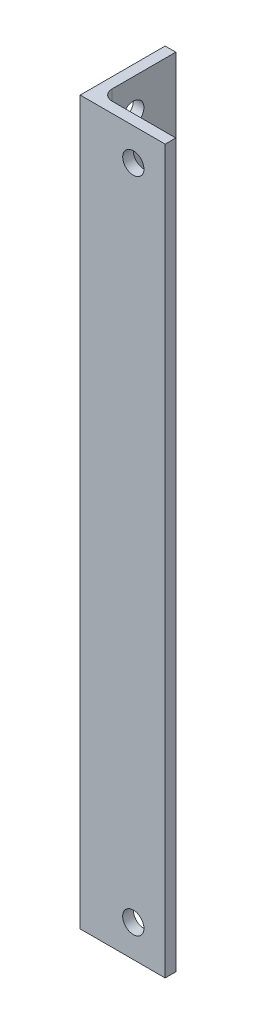
SolidWorks part; units mm, degrees
ref_plane "Front" through (0, 0, 0) normal (0, 0, 1) x (1, 0, 0)
ref_plane "Top" through (0, 0, 0) normal (0, 1, 0) x (1, 0, 0)
ref_plane "Right" through (0, 0, 0) normal (1, 0, 0) x (0, 0, -1)
sketch "Sketch1" plane through (0, 0, 0) normal (0, 1, 0) x (1, 0, 0)
  line L0 (0, 0) -> (0, -25.4)
  line L1 (0, -25.4) -> (25.4, -25.4)
  line L2 (25.4, -25.4) -> (25.4, -22.225)
  line L3 (25.4, -22.225) -> (3.175, -22.225)
  line L4 (3.175, -22.225) -> (3.175, 0)
  line L5 (3.175, 0) -> (0, 0)
  dimension "D1" = 3.175
  dimension "D2" = 25.4
  dimension "D3" = 25.4
  dimension "D4" = 3.175
extrude "Boss-Extrude1" add sketch "Sketch1" along normal blind 215.9
fillet "Fillet1" radius 3.175 1 edges at (3.175, 107.95, 22.225)
sketch "Sketch2" plane through (0, 0, 22.225) normal (0, 0, -1) x (-1, 0, 0)
  line L0 (-25.4, 215.9) -> (-25.4, 0) construction
  line L1 (-25.4, 215.9) -> (-6.35, 215.9) construction
  circle A0 centre (-15.875, 206.248) radius 3.175
  dimension "D1" = 6.35
  dimension "D2" = 9.525
  dimension "D3" = 9.652
extrude "Cut-Extrude1" cut sketch "Sketch2" against normal through all
sketch "Sketch3" plane through (0, 0, 22.225) normal (0, 0, -1) x (-1, 0, 0)
  line L0 (-25.4, 215.9) -> (-25.4, 0) construction
  line L1 (-25.4, 0) -> (-6.35, 0) construction
  circle A0 centre (-15.875, 9.652) radius 3.175
  dimension "D1" = 6.35
  dimension "D2" = 9.525
  dimension "D3" = 9.652
extrude "Cut-Extrude2" cut sketch "Sketch3" against normal through all
sketch "Sketch4" plane through (3.175, 0, 0) normal (1, 0, 0) x (0, 0, -1)
  line L1 (-19.05, 215.9) -> (0, 215.9) construction
  line L3 (0, 215.9) -> (0, 0) construction
  circle A0 centre (-12.7, 206.375) radius 3.175
  dimension "D1" = 6.35
  dimension "D2" = 9.525
  dimension "D3" = 12.7
extrude "Cut-Extrude3" cut sketch "Sketch4" against normal through all
sketch "Sketch5" plane through (3.175, 0, 0) normal (1, 0, 0) x (0, 0, -1)
  line L0 (-19.05, 0) -> (0, 0) construction
  line L1 (0, 215.9) -> (0, 0) construction
  circle A0 centre (-12.7, 9.525) radius 3.175
  dimension "D1" = 6.35
  dimension "D2" = 9.525
  dimension "D3" = 12.7
extrude "Cut-Extrude4" cut sketch "Sketch5" against normal through all
